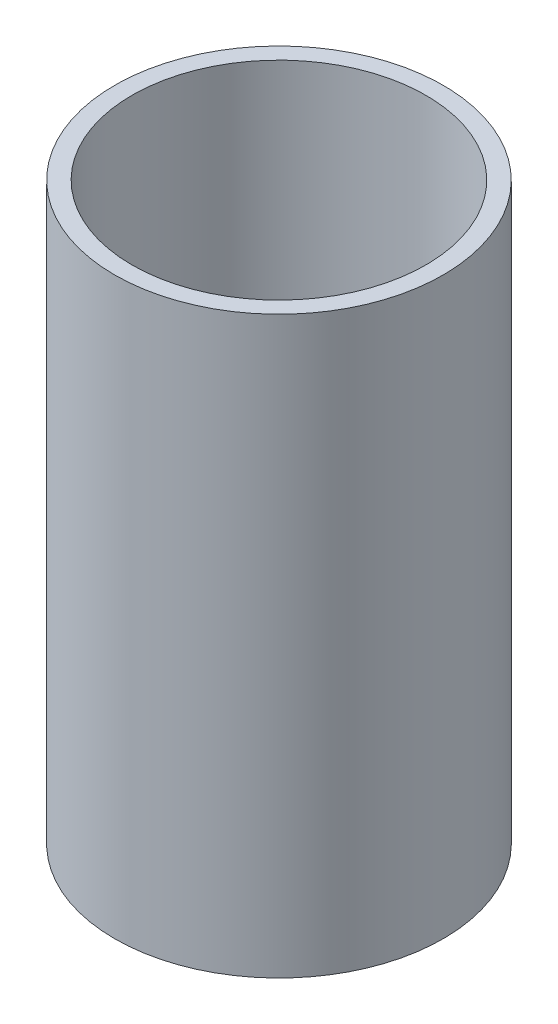
SolidWorks part; units mm, degrees
ref_plane "Płaszczyzna przednia" through (0, 0, 0) normal (0, 0, 1) x (1, 0, 0)
ref_plane "Płaszczyzna górna" through (0, 0, 0) normal (0, 1, 0) x (1, 0, 0)
ref_plane "Płaszczyzna prawa" through (0, 0, 0) normal (1, 0, 0) x (0, 0, -1)
sketch3d "Szkic 3D1"
  line L0 (0, 0, 0) -> (0, 200, 0)
  dimension "D1" = 200
other "Rura grubościenna; standardowa s40 PIPE 4 SCH 40(1)"
ref_plane "Płaszczyzna1" through (0, 0, 0) normal (0, 1, 0) x (1, 0, 0)
sketch "Sketch13" plane through (0, 0, 0) normal (0, 1, 0) x (1, 0, 0)
  circle A0 centre (0, 0) radius 51.1302
  circle A1 centre (0, 0) radius 57.15
  point P3 (0, 0)
  dimension "In_dia" = 102.2604
  dimension "Out_dia" = 114.3
